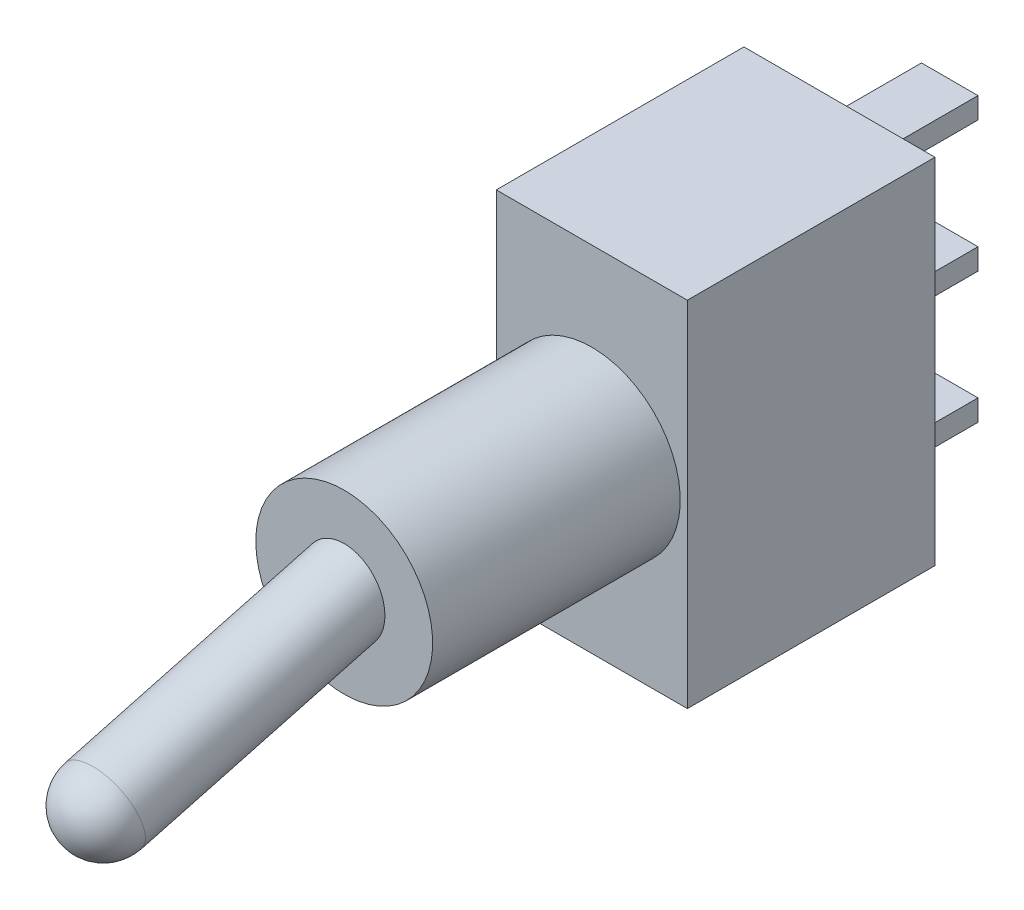
SolidWorks part; units mm, degrees
ref_plane "Plan de face" through (0, 0, 0) normal (0, 0, 1) x (1, 0, 0)
ref_plane "Plan de dessus" through (0, 0, 0) normal (0, 1, 0) x (1, 0, 0)
ref_plane "Plan de droite" through (0, 0, 0) normal (1, 0, 0) x (0, 0, -1)
sketch "Esquisse1" plane through (0, 0, 0) normal (0, 0, 1) x (1, 0, 0)
  line L1 (-3.43, 6.35) -> (3.43, 6.35)
  line L2 (-3.43, 6.35) -> (-3.43, -6.35)
  line L3 (-3.43, -6.35) -> (3.43, -6.35)
  line L4 (3.43, 6.35) -> (3.43, -6.35)
  line L5 (-3.43, 6.35) -> (3.43, -6.35) construction
  line L6 (-3.43, -6.35) -> (3.43, 6.35) construction
  point P0 (0, 0)
  dimension "D1" = 12.7
  dimension "D2" = 6.86
extrude "Boss.-Extru.1" add sketch "Esquisse1" against normal blind 8.89
sketch "Esquisse2" plane through (0, 0, 0) normal (0, 0, 1) x (1, 0, 0)
  circle A0 centre (0, 0) radius 3.175
  dimension "D1" = 6.35
extrude "Boss.-Extru.2" add sketch "Esquisse2" along normal blind 8.89
sketch "Esquisse3" plane through (0, 0, 0) normal (1, 0, 0) x (0, 0, -1)
  line L0 (-8.89, 0) -> (-24.8677, -4.2812) construction
  line L1 (-8.89, 3.175) -> (-8.89, -3.175) construction
  line L2 (0, 0) -> (-25.0079, 0) construction
  line L3 (-17.9129, -0.9062) -> (-8.89, 1.5115)
  line L4 (-8.89, 1.5115) -> (-8.5121, 0.1013)
  line L5 (-8.5121, 0.1013) -> (-18.9453, -2.6943)
  arc A0 (-18.9453, -2.6943) -> (-17.9129, -0.9062) centre (-17.535, -2.3164) cw
  dimension "D1" = 15
  dimension "D2" = 2.92
  dimension "D3" = 10.41
revolve "Révolution1" add sketch "Esquisse3" angle 360 about L0
sketch "Esquisse4" plane through (0, 0, -8.89) normal (0, 0, -1) x (-1, 0, 0)
  line L1 (-1.015, 0.38) -> (1.015, 0.38)
  line L2 (-1.015, 0.38) -> (-1.015, -0.38)
  line L3 (-1.015, -0.38) -> (1.015, -0.38)
  line L4 (1.015, 0.38) -> (1.015, -0.38)
  line L5 (-1.015, 0.38) -> (1.015, -0.38) construction
  line L6 (-1.015, -0.38) -> (1.015, 0.38) construction
  line L7 (-1.015, 5.08) -> (1.015, 5.08)
  line L8 (-1.015, 5.08) -> (-1.015, 4.32)
  line L9 (-1.015, 4.32) -> (1.015, 4.32)
  line L10 (1.015, 5.08) -> (1.015, 4.32)
  line L11 (-1.015, 5.08) -> (1.015, 4.32) construction
  line L12 (-1.015, 4.32) -> (1.015, 5.08) construction
  line L13 (-1.015, -4.32) -> (1.015, -4.32)
  line L14 (-1.015, -4.32) -> (-1.015, -5.08)
  line L15 (-1.015, -5.08) -> (1.015, -5.08)
  line L16 (1.015, -4.32) -> (1.015, -5.08)
  line L17 (-1.015, -4.32) -> (1.015, -5.08) construction
  line L18 (-1.015, -5.08) -> (1.015, -4.32) construction
  point P0 (0, 0)
  point P5 (0, 4.7)
  point P11 (0, -4.7)
  point P18 (0, 0)
  dimension "D1" = 0.76
  dimension "D2" = 2.03
  dimension "D3" = 0.76
  dimension "D4" = 2.03
  dimension "D5" = 0.76
  dimension "D6" = 2.03
  dimension "D7" = 4.7
  dimension "D8" = 4.7
extrude "Boss.-Extru.3" add sketch "Esquisse4" along normal blind 3.96
